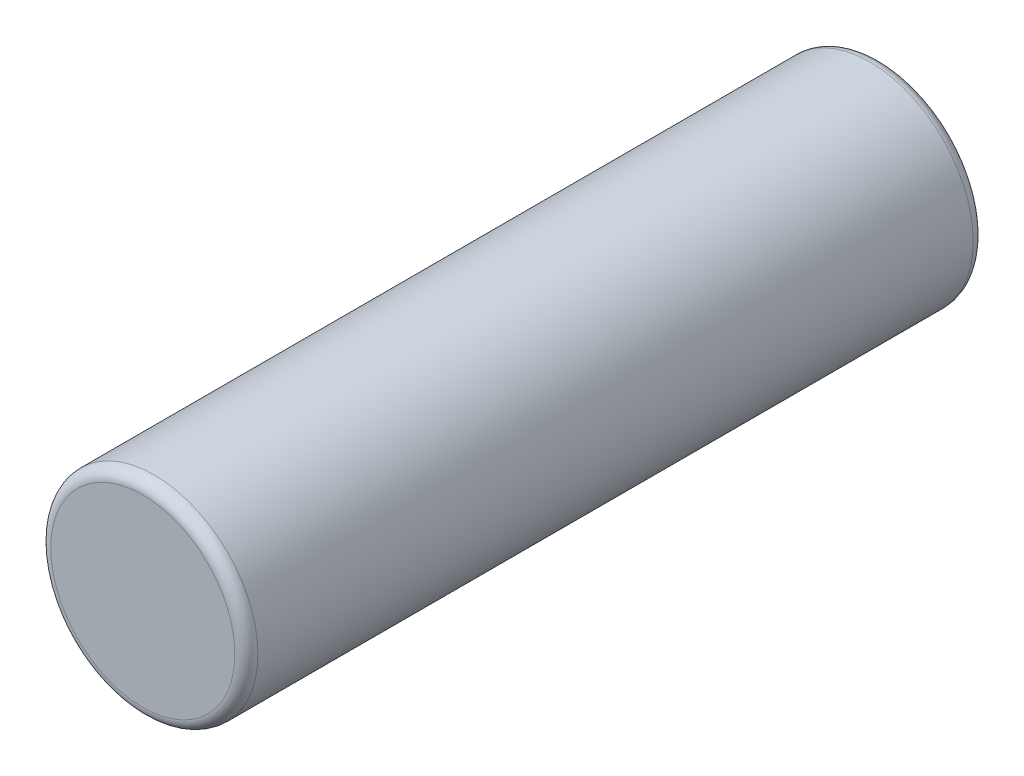
SolidWorks part; units mm, degrees
ref_plane "Front Plane" through (0, 0, 0) normal (0, 0, 1) x (1, 0, 0)
ref_plane "Top Plane" through (0, 0, 0) normal (0, 1, 0) x (1, 0, 0)
ref_plane "Right Plane" through (0, 0, 0) normal (1, 0, 0) x (0, 0, -1)
ref_plane "Plane1" through (0, -1.2088, 0) normal (0, -1, 0) x (1, 0, 0)
sketch "Sketch1" plane through (0, -1.2088, 0) normal (0, -1, 0) x (1, 0, 0)
  line L0 (6.1319, 64.15) -> (-1.8681, 64.15)
  line L1 (-1.8681, 64.15) -> (-1.8681, 0)
  line L2 (-1.8681, 0) -> (2.1319, 0)
  line L3 (2.6319, 0.5) -> (2.6319, 2)
  line L4 (3.1319, 2.5) -> (4.6319, 2.5)
  line L5 (4.6319, 2.5) -> (4.6319, 1.9365)
  line L6 (7.1319, 1) -> (7.1319, 63.15)
  line L7 (-1.8681, 64.1513) -> (-1.8681, -0.0029) construction
  arc A0 (2.1319, 0) -> (2.6319, 0.5) centre (2.1319, 0.5) ccw
  arc A1 (2.6319, 2) -> (3.1319, 2.5) centre (3.1319, 2) cw
  arc A2 (4.6319, 1.9365) -> (6.1319, 0) centre (6.6319, 1.9365) ccw
  arc A3 (6.1319, 0) -> (7.1319, 1) centre (6.1319, 1) ccw
  arc A4 (7.1319, 63.15) -> (6.1319, 64.15) centre (6.1319, 63.15) ccw
revolve "Revolve1" add sketch "Sketch1" angle 360 about L7
